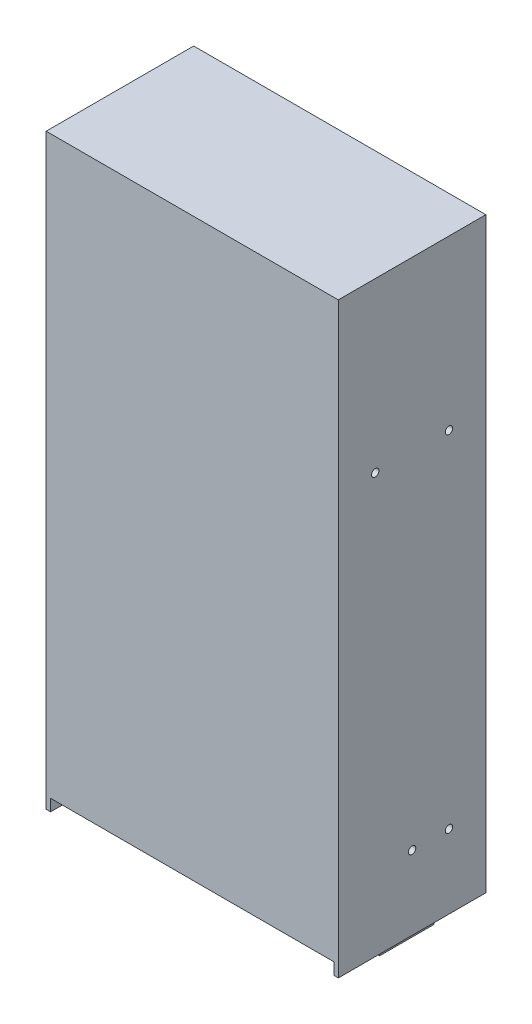
SolidWorks part; units mm, degrees
ref_plane "Front Plane" through (0, 0, 0) normal (0, 0, 1) x (1, 0, 0)
ref_plane "Top Plane" through (0, 0, 0) normal (0, 1, 0) x (1, 0, 0)
ref_plane "Right Plane" through (0, 0, 0) normal (1, 0, 0) x (0, 0, -1)
sketch "Sketch1" plane through (0, 0, 0) normal (0, 0, 1) x (1, 0, 0)
  line L1 (-49.5, -99.5) -> (49.5, -99.5)
  line L2 (-49.5, -99.5) -> (-49.5, 99.5)
  line L3 (-49.5, 99.5) -> (49.5, 99.5)
  line L4 (49.5, -99.5) -> (49.5, 99.5)
  line L5 (-49.5, -99.5) -> (49.5, 99.5) construction
  line L6 (-49.5, 99.5) -> (49.5, -99.5) construction
  point P0 (0, 0)
  dimension "D1" = 99
  dimension "D2" = 199
extrude "Boss-Extrude1" add sketch "Sketch1" along normal blind 50
sketch "Sketch2" plane through (0, 0, 50) normal (0, 0, 1) x (1, 0, 0)
  line L0 (-49.5, -99.5) -> (49.5, -99.5) construction
  line L1 (48, -99.5) -> (-48, -99.5)
  line L2 (48, -99.5) -> (48, -95.5)
  line L3 (48, -95.5) -> (-48, -95.5)
  line L4 (-48, -99.5) -> (-48, -95.5)
  line L6 (49.5, -99.5) -> (49.5, 99.5) construction
  line L7 (48, -95.5) -> (49.5, -95.5) construction
  line L8 (-48, -95.5) -> (-49.5, -95.5) construction
  line L9 (-49.5, 99.5) -> (-49.5, -99.5) construction
  dimension "D1" = 1.5
  dimension "D2" = 4
extrude "Cut-Extrude1" cut sketch "Sketch2" against normal offset from surface (48.5 mm away) 1.5 up to face at (0, 0, 0)
sketch "Sketch3" plane through (0, -99.5, 0) normal (0, -1, 0) x (1, 0, 0)
  line L0 (48, 1.5) -> (-48, 1.5) construction
  line L1 (39, 1.5) -> (-43.4555, 1.5)
  line L2 (39, 1.5) -> (39, 25.5)
  line L3 (39, 25.5) -> (-19, 25.5)
  line L4 (-19, 10.5) -> (-19, 25.5)
  line L5 (48, 1.5) -> (48, 50) construction
  line L6 (-48, 1.5) -> (-43.4555, 1.5)
  line L7 (-48, 1.5) -> (-48, 10.5)
  line L8 (-48, 10.5) -> (-19, 10.5)
  line L9 (-48, 1.5) -> (-48, 50) construction
  line L10 (48, 1.5) -> (-48, 1.5) construction
  dimension "D1" = 9
  dimension "D2" = 58
  dimension "D3" = 24
  dimension "D4" = 9
extrude "Boss-Extrude2" add sketch "Sketch3" against normal up to next
sketch "Sketch4" plane through (0, 99.5, 0) normal (0, 1, 0) x (1, 0, 0)
  line L0 (-49.5, -50) -> (-49.5, 0) construction
  line L1 (-49.5, -50) -> (48, -50)
  line L2 (-49.5, -50) -> (-49.5, -11.5495)
  line L3 (-37, -11.5) -> (48, -11.5)
  line L4 (48, -50) -> (48, -11.5)
  line L5 (-49.5, -1.5) -> (-37, -1.5)
  line L6 (-49.5, -1.5) -> (-49.5, -11.5495)
  line L7 (49.5, 0) -> (-49.5, 0) construction
  line L8 (-37, -1.5) -> (-37, -11.5)
  line L9 (49.5, -50) -> (49.5, 0) construction
  dimension "D1" = 11.5
  dimension "D2" = 1.5
  dimension "D3" = 1.5
  dimension "D4" = 12.5
extrude "Cut-Extrude2" [suppressed] cut sketch "Sketch4" against normal blind 5
sketch "Sketch5" [suppressed] plane through (49.5, 0, 0) normal (1, 0, 0) x (0, 0, -1)
  line L0 (-45.7, 96.2) -> (-45.7, 99.5)
  line L1 (-50, 99.5) -> (0, 99.5) construction
  line L2 (-45.7, 99.5) -> (-42.3, 99.5)
  line L3 (-42.3, 99.5) -> (-42.3, 96.2)
  line L4 (-24.7, 96.2) -> (-24.7, 99.5)
  line L5 (-24.7, 99.5) -> (-21.3, 99.5)
  line L6 (-21.3, 99.5) -> (-21.3, 96.2)
  line L7 (-50, 94.5) -> (-11.5, 94.5) construction
  line L8 (-50, -99.5) -> (-50, 99.5) construction
  line L9 (-50, -99.5) -> (0, -99.5) construction
  arc A0 (-45.7, 96.2) -> (-42.3, 96.2) centre (-44, 96.2) ccw
  arc A1 (-24.7, 96.2) -> (-21.3, 96.2) centre (-23, 96.2) ccw
  circle A2 centre (-44, -93.5) radius 1.7402
  circle A3 centre (-33, -93.5) radius 1.7402
  dimension "D1" = 1.7
  dimension "D2" = 6
  dimension "D3" = 27
  dimension "D4" = 6
  dimension "D5" = 6
  dimension "D6" = 17
extrude "Cut-Extrude3" [suppressed] cut sketch "Sketch5" against normal up to next
sketch "Sketch7" plane through (0, -99.5, 0) normal (0, -1, 0) x (1, 0, 0)
  line L1 (39, 25.5) -> (-19, 25.5)
  line L2 (39, 25.5) -> (39, 7)
  line L3 (39, 7) -> (-19, 7)
  line L4 (-19, 25.5) -> (-19, 7)
  line L8 (-49.5, 0) -> (49.5, 0) construction
  dimension "D1" = 7
extrude "Boss-Extrude3" add sketch "Sketch7" along normal blind 11
sketch "Sketch8" [suppressed] plane through (0, 0, 0) normal (0, 0, -1) x (-1, 0, 0)
  line L0 (41.8, 96.2) -> (41.8, 99.5)
  line L1 (-49.5, 99.5) -> (49.5, 99.5) construction
  line L2 (41.8, 99.5) -> (45.2, 99.5)
  line L3 (45.2, 99.5) -> (45.2, 96.2)
  line L4 (49.5, 99.5) -> (49.5, -99.5) construction
  line L5 (37, 94.5) -> (49.5, 94.5) construction
  arc A0 (41.8, 96.2) -> (45.2, 96.2) centre (43.5, 96.2) ccw
  dimension "D1" = 1.7
  dimension "D2" = 6
extrude "Cut-Extrude5" [suppressed] cut sketch "Sketch8" against normal up to next
sketch "Sketch9" plane through (0, 0, 1.5) normal (0, 0, 1) x (1, 0, 0)
  line L0 (49.5, -99.5) -> (49.5, 99.5) construction
  line L1 (39, -99.5) -> (48, -99.5) construction
  circle A0 centre (11.5, -79.5) radius 1.25
  circle A1 centre (-39.5, -79.5) radius 1.25
  circle A2 centre (-39.5, 88.5) radius 1.25
  circle A3 centre (39.5, 88.5) radius 1.25
  dimension "D1" = 2.5
  dimension "D4" = 51
  dimension "D5" = 79
  dimension "D6" = 168
  dimension "D2" = 38
  dimension "D3" = 20
extrude "Cut-Extrude6" cut sketch "Sketch9" against normal through all
chamfer "Chamfer1" [suppressed] distance 5 angle 45
fillet "Fillet1" [suppressed] radius 4
sketch "Sketch10" plane through (49.5, 0, 0) normal (1, 0, 0) x (0, 0, -1)
  line L2 (-50, -99.5) -> (0, -99.5) construction
  line L3 (0, -99.5) -> (0, 99.5) construction
  circle A0 centre (-37.5, 42.5) radius 1.25
  circle A1 centre (-12.5, 42.5) radius 1.25
  circle A2 centre (-25, -74.5) radius 1.25
  circle A3 centre (-12.5, -74.5) radius 1.25
  dimension "D5" = 25
  dimension "D6" = 2.5
  dimension "D1" = 142
  dimension "D2" = 25
  dimension "D3" = 12.5
  dimension "D4" = 25
extrude "Cut-Extrude7" cut sketch "Sketch10" against normal blind 5
sketch "Sketch11" plane through (-49.5, 0, 0) normal (-1, 0, 0) x (0, 0, 1)
  circle A0 centre (12.5, -74.5) radius 1.25
  circle A1 centre (12.5, 42.5) radius 1.25
  circle A2 centre (12.5, 42.5) radius 1.25 construction
  circle A3 centre (12.5, -74.5) radius 1.25 construction
extrude "Cut-Extrude8" cut sketch "Sketch11" against normal blind 10
